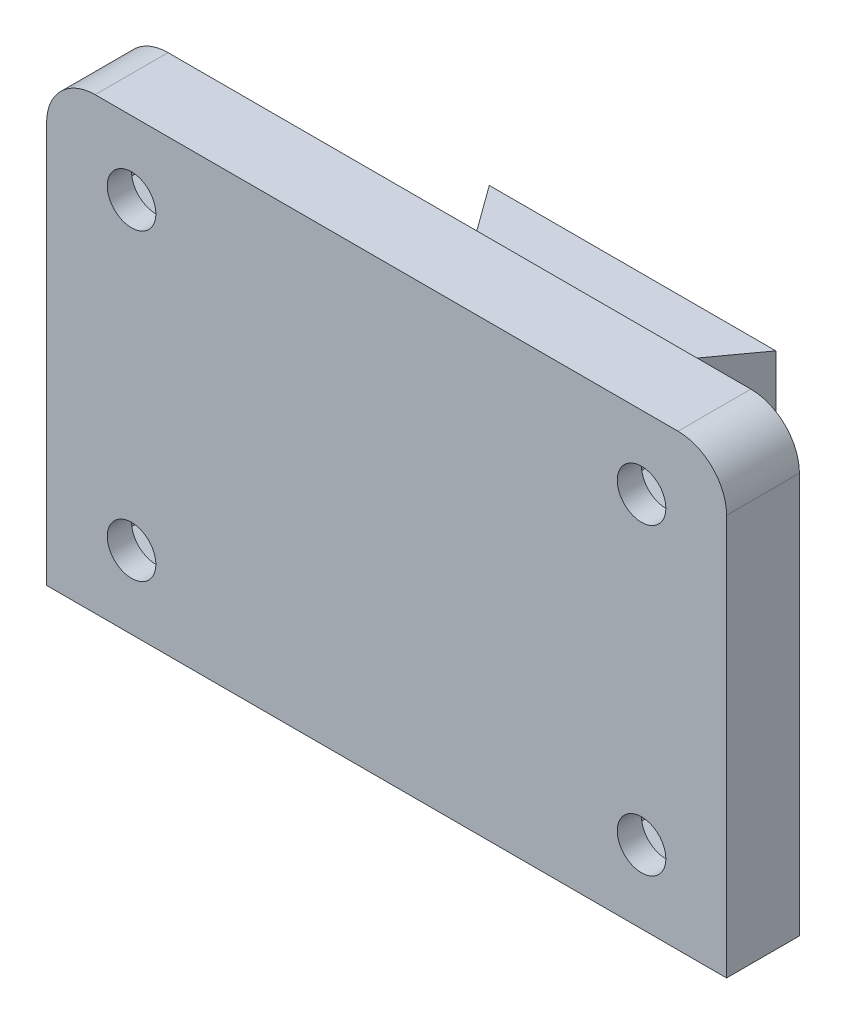
SolidWorks part; units mm, degrees
ref_plane "Front Plane" through (0, 0, 0) normal (0, 0, 1) x (1, 0, 0)
ref_plane "Top Plane" through (0, 0, 0) normal (0, 1, 0) x (1, 0, 0)
ref_plane "Right Plane" through (0, 0, 0) normal (1, 0, 0) x (0, 0, -1)
sketch "Sketch1" plane through (0, 0, 0) normal (0, 1, 0) x (1, 0, 0)
  line L0 (-2.9, 0) -> (2.9, 0)
  line L1 (-5.9, -4.1291) -> (5.9, -4.1291)
  line L2 (-5.9, -4.1291) -> (-5.9, 4.1291)
  line L3 (-5.9, 4.1291) -> (5.9, 4.1291)
  line L4 (5.9, -4.1291) -> (5.9, 4.1291)
  line L5 (-5.9, -4.1291) -> (5.9, 4.1291) construction
  line L6 (-5.9, 4.1291) -> (5.9, -4.1291) construction
  line L7 (2.9, 0) -> (5.9, 4.1291)
  line L8 (-2.9, 0) -> (-5.9, 4.1291)
  point P0 (0, 0)
  dimension "D1" = 5.8
  dimension "D2" = 126
  dimension "D3" = 126
  dimension "D4" = 11.8
extrude "Dovetail" add sketch "Sketch1" along normal blind 8 contours L8 L0 L7 L3
sketch "Sketch2" plane through (0, 0, 0) normal (0, 0, 1) x (1, 0, 0)
  line L0 (0, 0) -> (0, 8) construction
  line L1 (-2.9, 0) -> (2.9, 0) construction
  line L2 (-2.9, 8) -> (2.9, 8) construction
  line L4 (-1.6752, 0) -> (1.6752, 0)
  line L5 (-1.6752, 0) -> (-1.6752, 8)
  line L6 (-1.6752, 8) -> (1.6752, 8)
  line L7 (1.6752, 0) -> (1.6752, 8)
  line L8 (-1.6752, 0) -> (1.6752, 8) construction
  line L9 (-1.6752, 8) -> (1.6752, 0) construction
  point P6 (0, 4)
  point P11 (-1.7568, 10)
extrude "Stem" add sketch "Sketch2" along normal blind 3
sketch "Sketch3" plane through (0, 0, 3) normal (0, 0, 1) x (1, 0, 0)
  line L0 (0, 8) -> (0, 0) construction
  line L1 (1.6752, 8) -> (-1.6752, 8) construction
  line L2 (-1.6752, 0) -> (1.6752, 0) construction
  line L4 (-14, -5.25) -> (14, -5.25)
  line L5 (-14, -5.25) -> (-14, 13.25)
  line L6 (-14, 13.25) -> (14, 13.25)
  line L7 (14, -5.25) -> (14, 13.25)
  line L8 (-14, -5.25) -> (14, 13.25) construction
  line L9 (-14, 13.25) -> (14, -5.25) construction
  point P6 (0, 4)
  dimension "D1" = 28
  dimension "D2" = 18.5
extrude "Camera Plate" add sketch "Sketch3" along normal blind 3
fillet "Fillet1" radius 2 4 edges at (0, 0, 3) (1.6752, 4, 3) (0, 8, 3) (-1.6752, 4, 3)
sketch "Sketch4" plane through (0, 0, 6) normal (0, 0, 1) x (1, 0, 0)
  line L0 (14, -5.25) -> (14, 13.25) construction
  line L4 (14, 13.25) -> (-14, 13.25) construction
  circle A0 centre (-10.5, 10.25) radius 1
  circle A1 centre (10.5, 10.25) radius 1
  circle A2 centre (10.5, -2.25) radius 1
  circle A3 centre (-10.5, -2.25) radius 1
  dimension "D1" = 2
  dimension "D2" = 2
  dimension "D3" = 2
  dimension "D4" = 2
  dimension "D5" = 21
  dimension "D6" = 21
  dimension "D7" = 21
  dimension "D8" = 12.5
  dimension "D9" = 3
  dimension "D10" = 12.5
  dimension "D11" = 3
  dimension "D12" = 3.5
extrude "Screw Holes" cut sketch "Sketch4" against normal up to surface (3 mm away) up to face at (0, 4, 3)
sketch "Sketch5" plane through (0, 0, 3) normal (0, 0, -1) x (-1, 0, 0)
  line L1 (-10.5, 12.5594) -> (-12.5, 11.4047)
  line L2 (-12.5, 11.4047) -> (-12.5, 9.0953)
  line L3 (-12.5, 9.0953) -> (-10.5, 7.9406)
  line L4 (-10.5, 7.9406) -> (-8.5, 9.0953)
  line L5 (-8.5, 9.0953) -> (-8.5, 11.4047)
  line L6 (-8.5, 11.4047) -> (-10.5, 12.5594)
  line L7 (10.5, 12.5594) -> (8.5, 11.4047)
  line L8 (8.5, 11.4047) -> (8.5, 9.0953)
  line L9 (8.5, 9.0953) -> (10.5, 7.9406)
  line L10 (10.5, 7.9406) -> (12.5, 9.0953)
  line L11 (12.5, 9.0953) -> (12.5, 11.4047)
  line L12 (12.5, 11.4047) -> (10.5, 12.5594)
  line L13 (-10.5, -4.5594) -> (-8.5, -3.4047)
  line L14 (-8.5, -3.4047) -> (-8.5, -1.0953)
  line L15 (-8.5, -1.0953) -> (-10.5, 0.0594)
  line L16 (-10.5, 0.0594) -> (-12.5, -1.0953)
  line L17 (-12.5, -1.0953) -> (-12.5, -3.4047)
  line L18 (-12.5, -3.4047) -> (-10.5, -4.5594)
  line L19 (10.5, -4.5594) -> (12.5, -3.4047)
  line L20 (12.5, -3.4047) -> (12.5, -1.0953)
  line L21 (12.5, -1.0953) -> (10.5, 0.0594)
  line L22 (10.5, 0.0594) -> (8.5, -1.0953)
  line L23 (8.5, -1.0953) -> (8.5, -3.4047)
  line L24 (8.5, -3.4047) -> (10.5, -4.5594)
  circle A0 centre (-10.5, 10.25) radius 2 construction
  circle A1 centre (10.5, 10.25) radius 2 construction
  circle A2 centre (-10.5, -2.25) radius 2 construction
  circle A3 centre (10.5, -2.25) radius 2 construction
  point P28 (-8.5, 10.25)
  dimension "D1" = 4
  dimension "D2" = 4
  dimension "D3" = 4
  dimension "D4" = 4
extrude "Nut Holes" cut sketch "Sketch5" against normal blind 2
fillet "Fillet2" radius 2 2 edges at (14, 13.25, 4.5) (-14, 13.25, 4.5)
